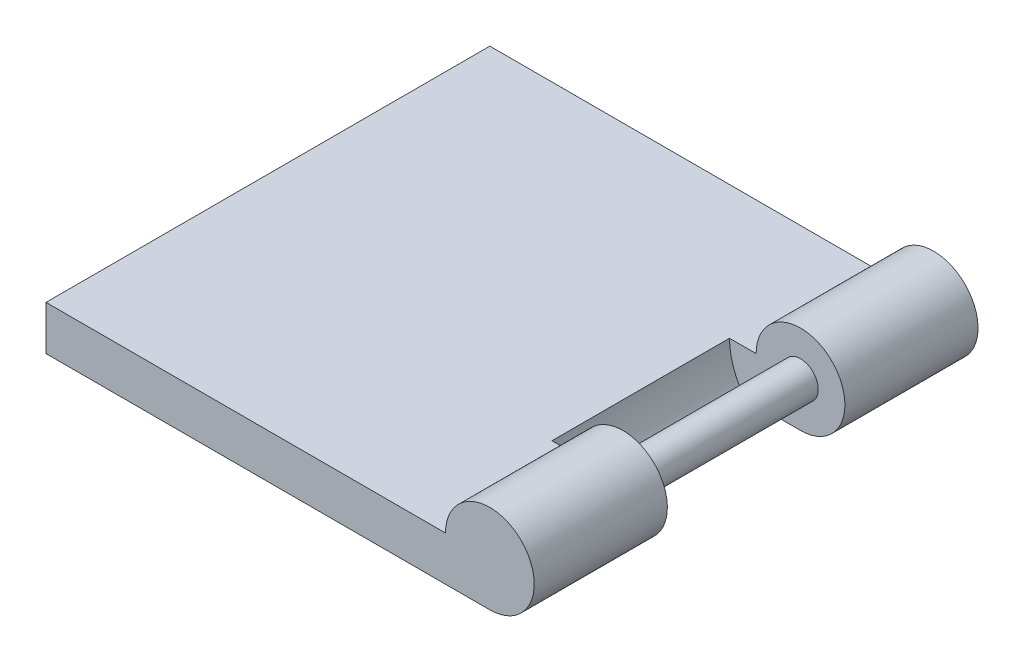
SolidWorks part; units mm, degrees
ref_plane "Front Plane" through (0, 0, 0) normal (0, 0, 1) x (1, 0, 0)
ref_plane "Top Plane" through (0, 0, 0) normal (0, 1, 0) x (1, 0, 0)
ref_plane "Right Plane" through (0, 0, 0) normal (1, 0, 0) x (0, 0, -1)
sketch "Sketch2" plane through (0, 0, 0) normal (0, 0, 1) x (1, 0, 0)
  line L1 (0, 0) -> (-50, 0)
  line L2 (0, 0) -> (0, -5)
  line L3 (0, -5) -> (-50, -5)
  line L4 (-50, 0) -> (-50, -5)
  point P5 (0, 0)
  point P6 (0, 0)
extrude "Boss-Extrude1" add sketch "Sketch2" against normal blind 50 contours L1 L4 L3 L2
sketch "Sketch3" plane through (0, 0, 0) normal (0, 0, 1) x (1, 0, 0)
  circle A0 centre (0, 0) radius 8
extrude "Cut-Extrude1" cut sketch "Sketch3" against normal blind 50 contours A0
sketch "Sketch4" plane through (0, 0, 0) normal (0, 0, 1) x (1, 0, 0)
  circle A0 centre (0, 0) radius 5
extrude "Boss-Extrude2" add sketch "Sketch4" against normal blind 50 separate body contours A0
ref_plane "Plane1" through (0, 0, -15) normal (0, 0, 1) x (1, 0, 0)
sketch "Sketch6" plane through (0, 0, -15) normal (0, 0, 1) x (1, 0, 0)
  circle A0 centre (0, 0) radius 5
extrude "Cut-Extrude2" cut sketch "Sketch6" against normal blind 20
sketch "Sketch7" plane through (0, 0, 0) normal (0, 0, 1) x (1, 0, 0)
  line L1 (0, 0) -> (-10, 0)
  line L2 (0, 0) -> (0, -5)
  line L3 (0, -5) -> (-10, -5)
  line L4 (-10, 0) -> (-10, -5)
  point P4 (0, 0)
  point P5 (3.3421, 0)
  point P6 (0, 0)
extrude "Boss-Extrude3" add sketch "Sketch7" against normal blind 15
pattern_linear "LPattern1" count 2 spacing 35 along (0, 0, -1) of "Boss-Extrude3"
sketch "Sketch8" plane through (0, 0, 0) normal (0, 0, 1) x (1, 0, 0)
  circle A0 centre (0, 0) radius 2
extrude "Boss-Extrude4" add sketch "Sketch8" against normal blind 50
